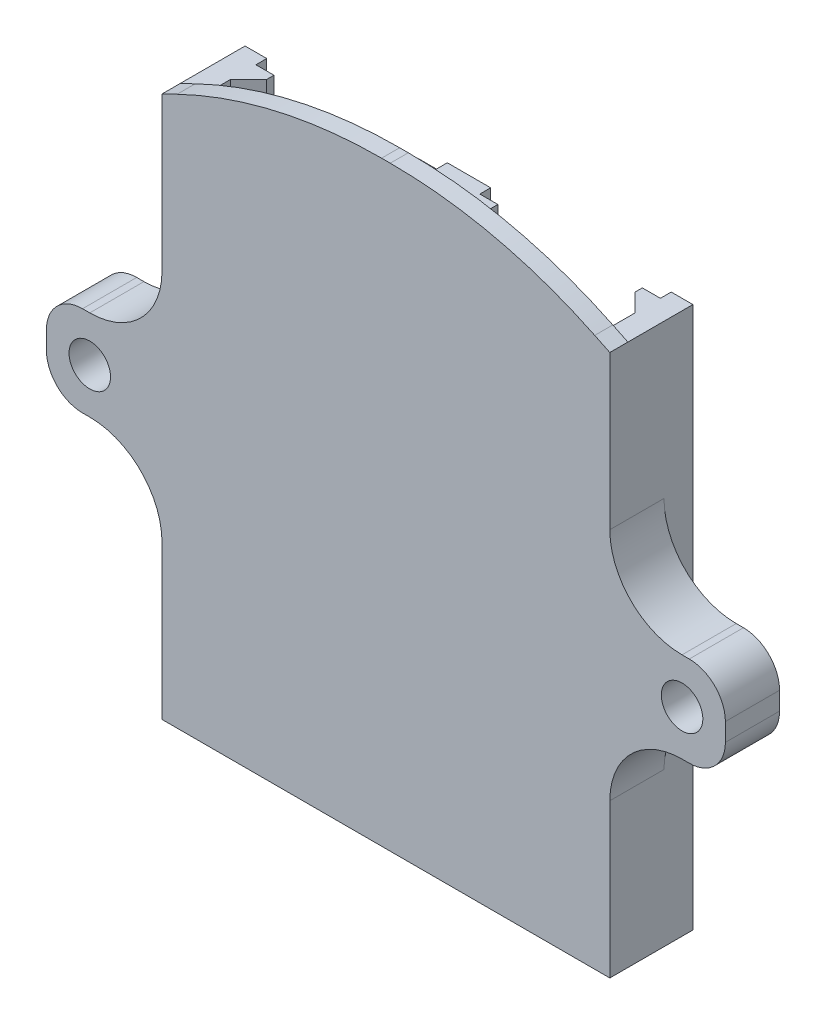
SolidWorks part; units mm, degrees
ref_plane "Přední rovina" through (0, 0, 0) normal (0, 0, 1) x (1, 0, 0)
ref_plane "Horní rovina" through (0, 0, 0) normal (0, 1, 0) x (1, 0, 0)
ref_plane "Pravá rovina" through (0, 0, 0) normal (1, 0, 0) x (0, 0, -1)
sketch "Skica1" plane through (0, 0, 0) normal (0, 1, 0) x (1, 0, 0)
  line L0 (-5, 0) -> (5, 0)
  line L1 (0, -1000) -> (0, 49000) construction
  line L2 (-5, 0) -> (-5, 1.6)
  line L3 (-5, 1.6) -> (-4, 2.6)
  line L4 (-4, 2.6) -> (-4, 3)
  line L6 (-6.2, 3.6) -> (-6.2, -1)
  line L7 (-6.2, -1) -> (6.2, -1)
  line L8 (0, -1) -> (0, 0) construction
  line L9 (-4, 3) -> (-5, 3)
  line L10 (-5, 3) -> (-5, 3.6)
  line L11 (-5, 3.6) -> (-6.2, 3.6)
  line L12 (5, 0) -> (5, 1.6)
  line L13 (5, 1.6) -> (4, 2.6)
  line L14 (4, 2.6) -> (4, 3)
  line L15 (4, 3) -> (5, 3)
  line L16 (5, 3) -> (5, 3.6)
  line L17 (6.2, 3.6) -> (6.2, -1)
  line L18 (5, 3.6) -> (6.2, 3.6)
  dimension "D2" = 0.4
  dimension "D1" = 5
  dimension "D3" = 1
  dimension "D4" = 1.2
  dimension "D5" = 1
  dimension "D6" = 1.6
  dimension "D7" = 1
  dimension "D8" = 0.6
extrude "Přidat vysunutím1" add sketch "Skica1" along normal blind 30
sketch "Skica2" plane through (0, 0, 0) normal (0, 0, 1) x (1, 0, 0)
  line L0 (-6.2, 30) -> (-6.2, 0) construction
  line L14 (-10.6, 17.5) -> (-10.2, 17.5)
  line L15 (-12.6, 15.5) -> (-12.6, 14.5)
  line L16 (-10.6, 12.5) -> (-10.2, 12.5)
  line L19 (-6.2, 21.5) -> (-6.2, 8.5)
  circle A0 centre (-10.2, 15) radius 1.15
  arc A5 (-10.6, 12.5) -> (-12.6, 14.5) centre (-10.6, 14.5) cw
  arc A6 (-12.6, 15.5) -> (-10.6, 17.5) centre (-10.6, 15.5) cw
  arc A7 (-6.2, 21.5) -> (-10.2, 17.5) centre (-10.2, 21.5) cw
  arc A8 (-10.2, 12.5) -> (-6.2, 8.5) centre (-10.2, 8.5) cw
  point P4 (-6.2, 15)
  point P11 (-12.6, 12.5)
  point P14 (-12.6, 17.5)
  point P18 (-6.2, 17.5)
  dimension "D1" = 4
  dimension "D3" = 5
  dimension "D5" = 6.4
  dimension "D6" = 2
  dimension "D7" = 4
  dimension "D8" = 4
  dimension "D2" = 0
  dimension "D4" = 2.5
extrude "Přidat vysunutím2" add sketch "Skica2" along normal blind 1 and the other way blind 2
sketch "Skica3" plane through (0, 0, 1) normal (0, 0, 1) x (1, 0, 0)
  line L0 (6.2, 30) -> (6.2, 0) construction
  line L1 (-6.2, 30) -> (6.2, 30)
  line L4 (6.2, 30) -> (6.2, 33)
  line L5 (-6.2, 30) -> (-5.3648, 30.4041)
  line L6 (5.9598, 33) -> (6.2, 33)
  arc A0 (-5.3648, 30.4041) -> (5.9598, 33) centre (5.9598, 7) cw
  dimension "D3" = 26
  dimension "D1" = 0
extrude "Přidat vysunutím3" add sketch "Skica3" against normal blind 1 contours L1 L4 L6 A0 L5
mirror "Zrcadlit2" about plane through (6.2, 30, -3.6) normal (-1, 0, 0) of "Přidat vysunutím3", "Přidat vysunutím2", "Přidat vysunutím1"
